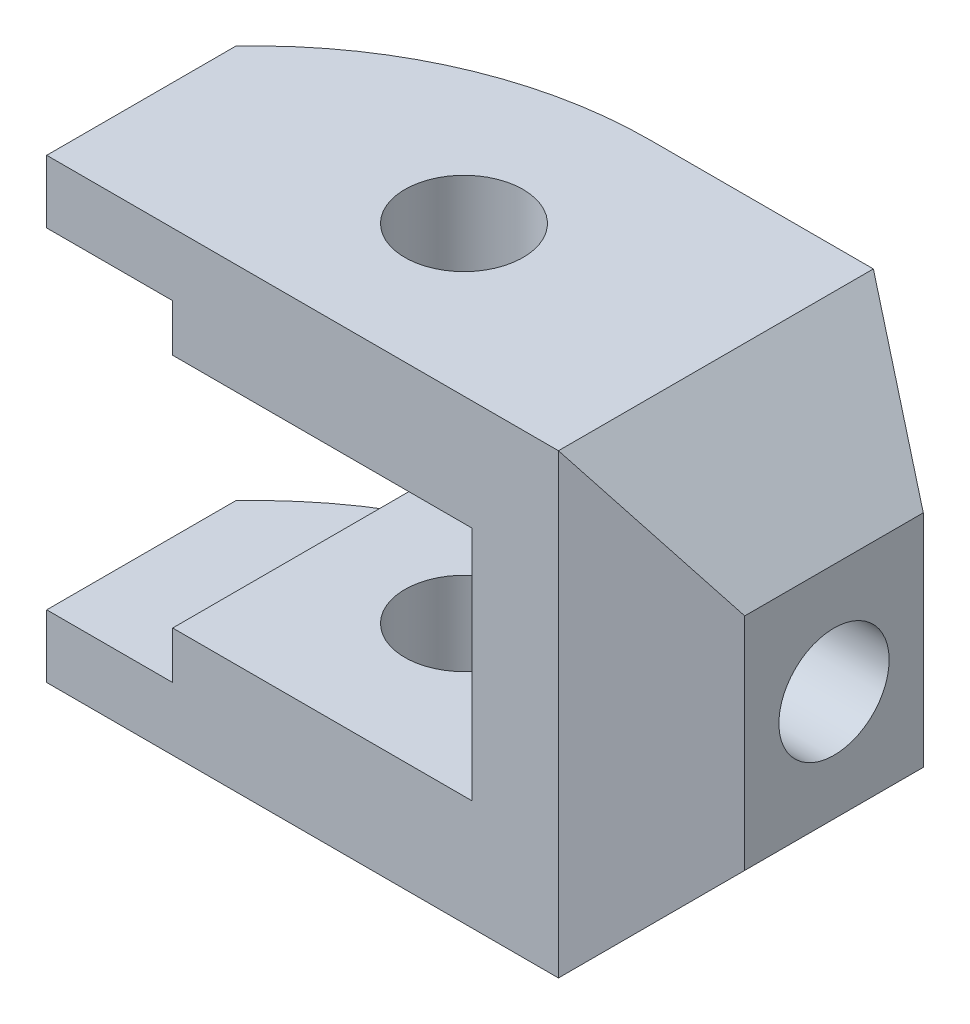
SolidWorks part; units mm, degrees
material "1060 Alloy"
ref_plane "Front Plane" through (0, 0, 0) normal (0, 0, 1) x (1, 0, 0)
ref_plane "Top Plane" through (0, 0, 0) normal (0, 1, 0) x (1, 0, 0)
ref_plane "Right Plane" through (0, 0, 0) normal (1, 0, 0) x (0, 0, -1)
sketch "Sketch1" plane through (0, 0, 0) normal (0, 1, 0) x (1, 0, 0)
  line L0 (0, 0) -> (65, 0)
  line L1 (65, 0) -> (80, 8.6603)
  line L2 (80, 8.6603) -> (80, 31.3397)
  line L3 (80, 31.3397) -> (65, 40)
  line L4 (65, 40) -> (36.6606, 40)
  line L5 (0, 0) -> (0, 24)
  arc A0 (0, 24) -> (36.6606, 40) centre (36.6606, -10) cw
  circle A1 centre (34, 19) radius 7.5
  point P11 (0, 0)
  dimension "D7" = 50
  dimension "D9" = 15
  dimension "D1" = 65
  dimension "D2" = 30
  dimension "D3" = 30
  dimension "D4" = 15
  dimension "D5" = 15
  dimension "D6" = 40
  dimension "D8" = 24
  dimension "D10" = 19
  dimension "D11" = 31
extrude "Boss-Extrude1" add sketch "Sketch1" along normal blind 58
sketch "Sketch2" plane through (0, 0, 0) normal (0, 0, 1) x (1, 0, 0)
  line L0 (0, 50) -> (16, 50)
  line L1 (0, 58) -> (0, 0) construction
  line L2 (16, 50) -> (16, 44)
  line L3 (16, 44) -> (54, 44)
  line L4 (54, 44) -> (54, 14)
  line L5 (54, 14) -> (16, 14)
  line L6 (16, 14) -> (16, 8)
  line L7 (16, 8) -> (0, 8)
  line L8 (0, 8) -> (0, 50)
  line L9 (0, 58) -> (65, 58) construction
  line L10 (65, 58) -> (65, 0) construction
  line L11 (0, 0) -> (65, 0) construction
  dimension "D1" = 8
  dimension "D2" = 6
  dimension "D3" = 11
  dimension "D4" = 16
  dimension "D5" = 8
extrude "Cut-Extrude1" cut sketch "Sketch2" against normal through all
sketch "Sketch4" plane through (0, 0, 0) normal (0, 0, 1) x (1, 0, 0)
  line L0 (65, 58) -> (80, 43)
  line L1 (80, 58) -> (80, 0) construction
  line L2 (80, 43) -> (80, 58)
  line L3 (80, 58) -> (65, 58)
  line L4 (65, 0) -> (80, 0)
  line L5 (80, 0) -> (80, 15)
  line L6 (80, 15) -> (65, 0)
  dimension "D1" = 45
  dimension "D2" = 45
extrude "Cut-Extrude2" cut sketch "Sketch4" against normal through all
sketch "Sketch5" plane through (80, 0, 0) normal (1, 0, 0) x (0, 0, -1)
  line L0 (40, 58) -> (40, 0) construction
  line L1 (40, 0) -> (0, 0) construction
  circle A0 centre (20, 29) radius 7
  dimension "D1" = 14
  dimension "D2" = 20
  dimension "D3" = 29
extrude "Cut-Extrude3" cut sketch "Sketch5" against normal through all
equation "\"a\"= 58mm"
equation "\"b\"= 40mm"
equation "\"c\"= 65mm"
